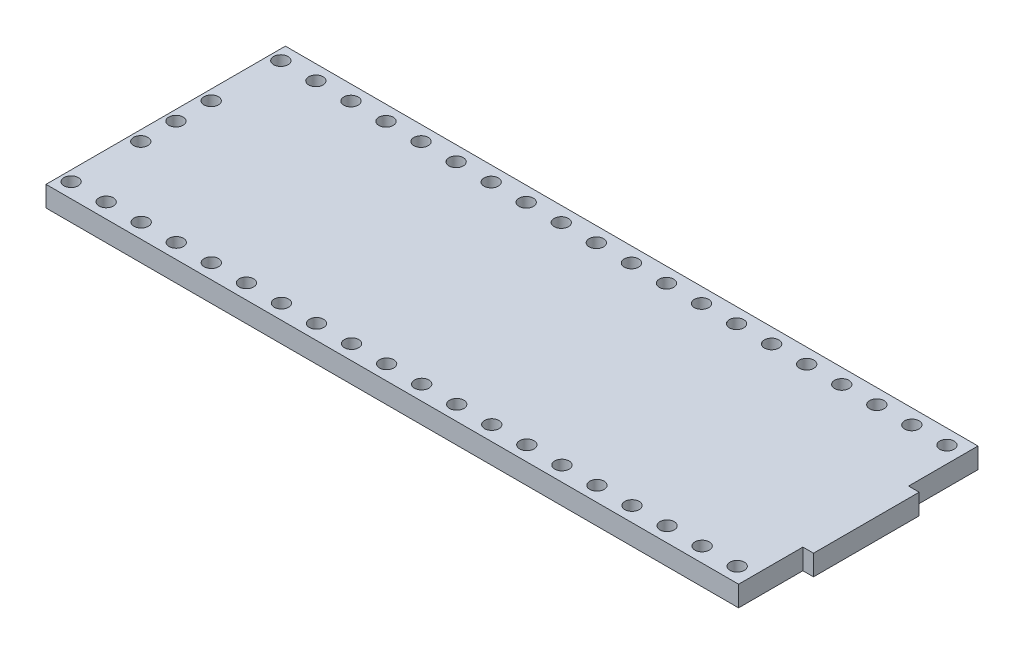
SolidWorks part; units mm, degrees
ref_plane "Front Plane" through (0, 0, 0) normal (0, 0, 1) x (1, 0, 0)
ref_plane "Top Plane" through (0, 0, 0) normal (0, 1, 0) x (1, 0, 0)
ref_plane "Right Plane" through (0, 0, 0) normal (1, 0, 0) x (0, 0, -1)
sketch "Sketch2" plane through (0, 0, 0) normal (0, 1, 0) x (1, 0, 0)
  line L1 (-26.1112, -8.89) -> (26.1112, -8.89)
  line L2 (-26.1112, -8.89) -> (-26.1112, 8.89)
  line L3 (-26.1112, 8.89) -> (26.1112, 8.89)
  line L4 (26.1112, -8.89) -> (26.1112, 8.89)
  line L5 (-26.1112, -8.89) -> (26.1112, 8.89) construction
  line L6 (-26.1112, 8.89) -> (26.1112, -8.89) construction
  point P0 (0, 0)
  dimension "D1" = 52.2224
  dimension "D2" = 17.78
extrude "Boss-Extrude1" add sketch "Sketch2" along normal blind 1.524
sketch "Sketch5" plane through (0, 1.524, 0) normal (0, 1, 0) x (1, 0, 0)
  line L0 (-26.1112, 8.89) -> (-26.1112, -8.89) construction
  line L1 (-26.1112, -8.89) -> (26.1112, -8.89) construction
  circle A0 centre (-25.3492, -7.7877) radius 0.5334
  dimension "D1" = 1.0668
  dimension "D2" = 0.762
  dimension "D3" = 1.1023
extrude "Cut-Extrude1" cut sketch "Sketch5" against normal up to next
pattern_linear "LPattern1" count 20 spacing 2.6035 along (1, 0, 0) of "Cut-Extrude1"
mirror "Mirror1" about plane through (0, 0, 0) normal (0, 0, 1) of "Cut-Extrude1", "LPattern1"
sketch "Sketch6" plane through (0, 1.524, 0) normal (0, 1, 0) x (1, 0, 0)
  line L0 (-26.1112, 8.89) -> (-26.1112, -8.89) construction
  line L1 (26.1112, -8.89) -> (25.3238, -8.89)
  line L2 (26.1112, -8.89) -> (26.1112, -4.1148)
  line L3 (26.1112, -4.1148) -> (25.3238, -4.1148)
  line L4 (25.3238, -8.89) -> (25.3238, -4.1148)
  line L5 (26.1112, 8.89) -> (25.3238, 8.89)
  line L6 (26.1112, 8.89) -> (26.1112, 3.7338)
  line L7 (26.1112, 3.7338) -> (25.3238, 3.7338)
  line L8 (25.3238, 8.89) -> (25.3238, 3.7338)
  dimension "D1" = 51.435
  dimension "D2" = 5.1562
  dimension "D3" = 4.7752
extrude "Cut-Extrude2" cut sketch "Sketch6" against normal up to next
sketch "Sketch7" plane through (0, 1.524, 0) normal (0, 1, 0) x (1, 0, 0)
  line L0 (-0.8382, 0) -> (0.8382, 0) construction
  line L1 (-26.1112, 8.89) -> (-26.1112, -8.89) construction
  circle A0 centre (-25.3492, 0) radius 0.5334
  circle A1 centre (-25.3492, 2.6162) radius 0.5334
  circle A2 centre (-25.3492, -2.6162) radius 0.5334
  circle A3 centre (-25.3492, -7.7877) radius 0.5334 construction
  dimension "D2" = 2.6162
  dimension "D3" = 2.6162
  dimension "D1" = 0.762
extrude "Cut-Extrude3" cut sketch "Sketch7" against normal up to next
